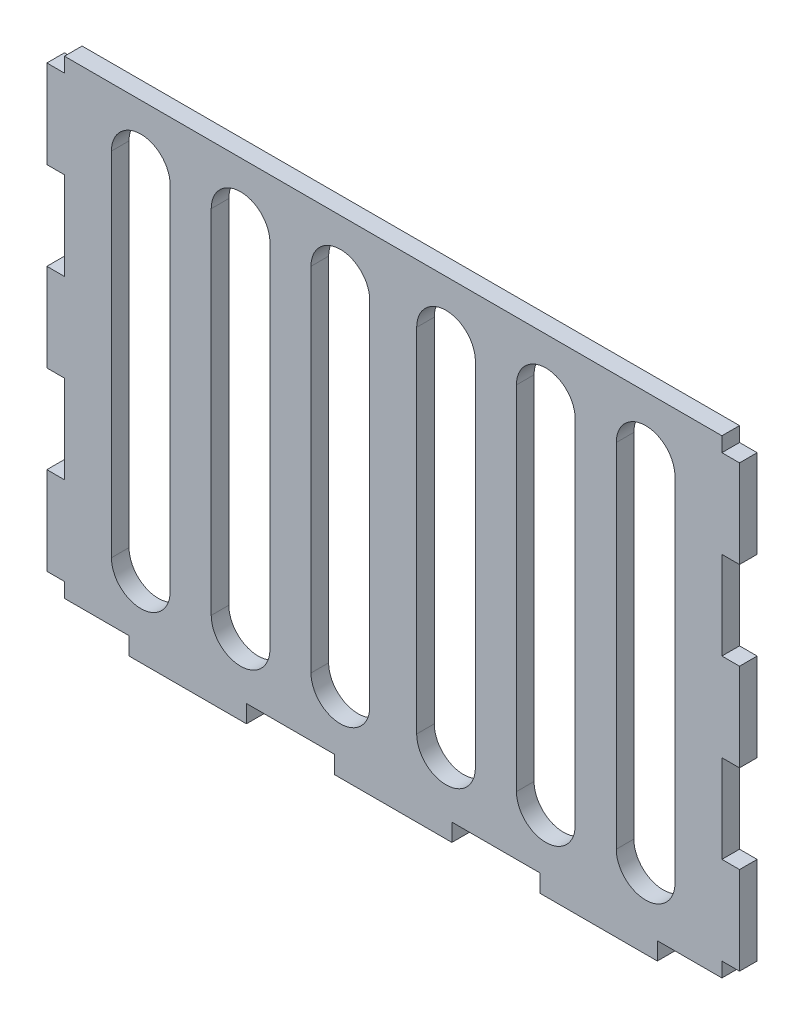
SolidWorks part; units mm, degrees
ref_plane "Front Plane" through (0, 0, 0) normal (0, 0, 1) x (1, 0, 0)
ref_plane "Top Plane" through (0, 0, 0) normal (0, 1, 0) x (1, 0, 0)
ref_plane "Right Plane" through (0, 0, 0) normal (1, 0, 0) x (0, 0, -1)
sketch "Sketch1" plane through (0, 0, 0) normal (0, 0, 1) x (1, 0, 0)
  line L0 (-43, -30) -> (-43, 30) construction
  line L1 (56, -40) -> (-56, -40)
  line L2 (56, -40) -> (56, 40)
  line L3 (56, 40) -> (-56, 40)
  line L4 (-56, -40) -> (-56, 40)
  line L5 (56, -40) -> (-56, 40) construction
  line L6 (56, 40) -> (-56, -40) construction
  line L7 (-48, -30) -> (-48, 30)
  line L8 (-38, -30) -> (-38, 30)
  line L9 (-26, -30) -> (-26, 30) construction
  line L10 (-31, -30) -> (-31, 30)
  line L11 (-21, -30) -> (-21, 30)
  line L12 (-9, -30) -> (-9, 30) construction
  line L13 (-14, -30) -> (-14, 30)
  line L14 (-4, -30) -> (-4, 30)
  line L15 (0, -55) -> (0, 55) construction
  line L16 (9, -30) -> (9, 30) construction
  line L17 (14, -30) -> (14, 30)
  line L18 (4, -30) -> (4, 30)
  line L19 (26, -30) -> (26, 30) construction
  line L20 (31, -30) -> (31, 30)
  line L21 (21, -30) -> (21, 30)
  line L22 (43, -30) -> (43, 30) construction
  line L23 (48, -30) -> (48, 30)
  line L24 (38, -30) -> (38, 30)
  line L25 (-25, -40) -> (-45, -40)
  line L26 (10, -43) -> (-10, -43)
  line L27 (10, -43) -> (10, -40)
  line L28 (10, -40) -> (-10, -40)
  line L29 (-10, -43) -> (-10, -40)
  line L30 (10, -43) -> (-10, -40) construction
  line L31 (10, -40) -> (-10, -43) construction
  line L32 (-59, -7.5) -> (-56, -7.5)
  line L33 (-59, -7.5) -> (-59, 7.5)
  line L34 (-59, 7.5) -> (-56, 7.5)
  line L35 (-56, -7.5) -> (-56, 7.5)
  line L36 (-59, -7.5) -> (-56, 7.5) construction
  line L37 (-59, 7.5) -> (-56, -7.5) construction
  line L38 (-56, 22.5) -> (-59, 22.5)
  line L39 (-56, 22.5) -> (-56, 37.5)
  line L40 (-56, 37.5) -> (-59, 37.5)
  line L41 (-59, 22.5) -> (-59, 37.5)
  line L42 (-56, 22.5) -> (-59, 37.5) construction
  line L43 (-56, 37.5) -> (-59, 22.5) construction
  line L44 (25, -43) -> (45, -43)
  line L45 (25, -43) -> (25, -40)
  line L46 (25, -40) -> (45, -40)
  line L47 (45, -43) -> (45, -40)
  line L48 (25, -43) -> (45, -40) construction
  line L49 (25, -40) -> (45, -43) construction
  line L50 (-45, -43) -> (-45, -40)
  line L51 (-25, -43) -> (-45, -43)
  line L52 (-25, -43) -> (-25, -40)
  line L53 (59, 7.5) -> (56, 7.5)
  line L54 (56, -7.5) -> (56, 7.5)
  line L55 (59, -7.5) -> (56, -7.5)
  line L56 (59, -7.5) -> (59, 7.5)
  line L57 (56, 37.5) -> (59, 37.5)
  line L58 (59, 22.5) -> (59, 37.5)
  line L59 (56, 22.5) -> (59, 22.5)
  line L60 (56, 22.5) -> (56, 37.5)
  line L61 (56, -22.5) -> (59, -22.5)
  line L62 (-56, -37.5) -> (-59, -37.5)
  line L63 (-56, -37.5) -> (-56, -22.5)
  line L64 (-56, -22.5) -> (-59, -22.5)
  line L65 (-59, -37.5) -> (-59, -22.5)
  line L66 (-56, -37.5) -> (-59, -22.5) construction
  line L67 (-56, -22.5) -> (-59, -37.5) construction
  line L68 (59, -37.5) -> (59, -22.5)
  line L69 (56, -37.5) -> (59, -37.5)
  line L70 (56, -37.5) -> (56, -22.5)
  arc A0 (-48, -30) -> (-38, -30) centre (-43, -30) ccw
  arc A1 (-38, 30) -> (-48, 30) centre (-43, 30) ccw
  arc A2 (-31, -30) -> (-21, -30) centre (-26, -30) ccw
  arc A3 (-21, 30) -> (-31, 30) centre (-26, 30) ccw
  arc A4 (-14, -30) -> (-4, -30) centre (-9, -30) ccw
  arc A5 (-4, 30) -> (-14, 30) centre (-9, 30) ccw
  arc A6 (14, -30) -> (4, -30) centre (9, -30) cw
  arc A7 (4, 30) -> (14, 30) centre (9, 30) cw
  arc A8 (31, -30) -> (21, -30) centre (26, -30) cw
  arc A9 (21, 30) -> (31, 30) centre (26, 30) cw
  arc A10 (48, -30) -> (38, -30) centre (43, -30) cw
  arc A11 (38, 30) -> (48, 30) centre (43, 30) cw
  point P0 (0, 0)
  point P8 (-43, 0)
  point P15 (-26, 0)
  point P20 (-9, 0)
  point P27 (-57.5, 0)
  point P33 (9, 0)
  point P40 (26, 0)
  point P47 (43, 0)
  point P52 (0, -41.5)
  point P60 (35, -41.5)
  point P61 (-57.5, 30)
  point P70 (0, 0)
  point P83 (-57.5, -30)
  dimension "D4" = 5
  dimension "D1" = 80
  dimension "D2" = 112
  dimension "D3" = 60
  dimension "D5" = 8
  dimension "D6" = 7
  dimension "D7" = 7
  dimension "D8" = 15
  dimension "D9" = 3
  dimension "D10" = 20
  dimension "D11" = 3
  dimension "D12" = 15
  dimension "D13" = 15
  dimension "D14" = 15
extrude "Boss-Extrude1" add sketch "Sketch1" along normal blind 3 contours L41 L38 L4 L40 | L4 L1 L2 L3 A5 L14 A4 L13 A3 L11 A2 L10 A1 L8 A0 L7 L18 A7 L17 A6 L21 A9 L20 A8 L24 A11 L23 A10 | L34 L33 L32 L4 | L51 L52 L1 L50 | L29 L26 L27 L1 | L44 L47 L1 L45 | L55 L56 L53 L2 | L2 L59 L58 L57 | L63 L62 L65 L64 | L61 L68 L69 L70
